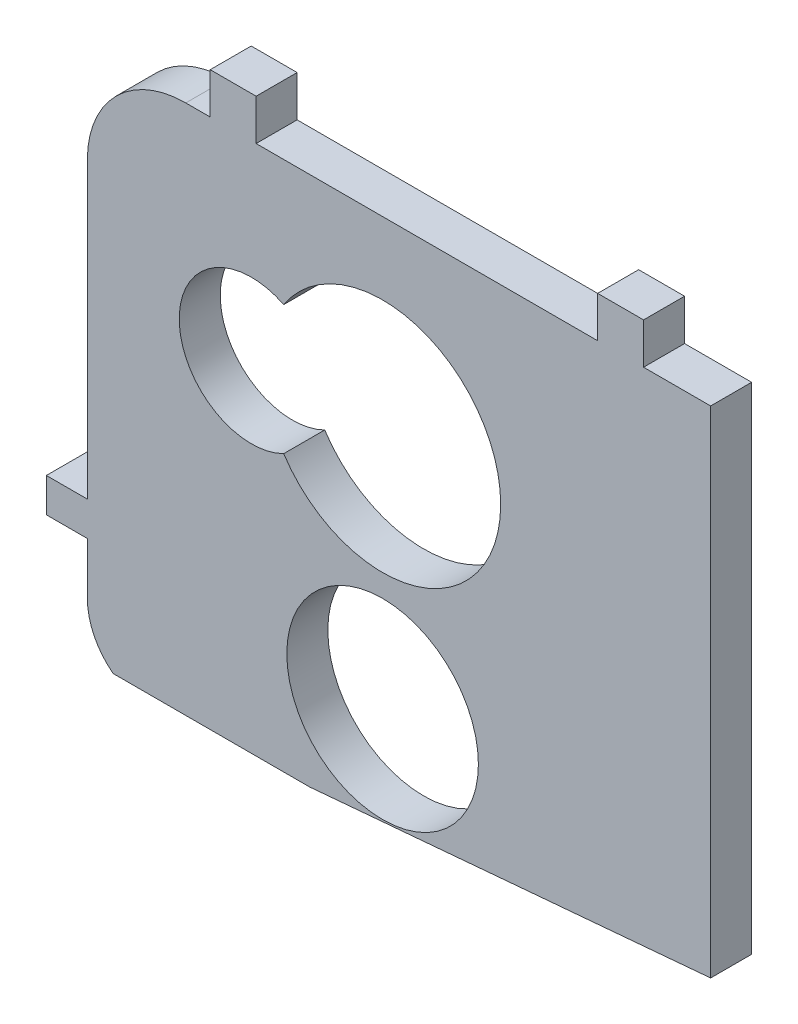
SolidWorks part; units mm, degrees
material "Balsa"
ref_plane "Front Plane" through (0, 0, 0) normal (0, 0, 1) x (1, 0, 0)
ref_plane "Top Plane" through (0, 0, 0) normal (0, 1, 0) x (1, 0, 0)
ref_plane "Right Plane" through (0, 0, 0) normal (1, 0, 0) x (0, 0, -1)
sketch "Sketch1" plane through (0, 0, 0) normal (0, 0, 1) x (1, 0, 0)
  line L0 (0, -1000.1535) -> (0, 48999.8465) construction
  line L1 (-2.8233, -4.0284) -> (-10.4313, -4.0284)
  line L2 (-1000, 0) -> (49000, 0) construction
  line L3 (12.7, 16.51) -> (-7.62, 16.51)
  line L4 (12.7, 16.51) -> (12.7, -2.6702)
  line L5 (8.3256, 18.0975) -> (10.1036, 18.0975)
  line L6 (12.7, -2.6702) -> (-8.6686, -4.5398)
  line L7 (-11.43, 12.7) -> (-11.43, -2.0094)
  line L8 (-6.6744, 16.51) -> (-4.8964, 16.51)
  line L9 (-6.6744, 16.51) -> (-6.6744, 18.0975)
  line L10 (-6.6744, 18.0975) -> (-4.8964, 18.0975)
  line L11 (-4.8964, 16.51) -> (-4.8964, 18.0975)
  line L12 (-11.43, 0) -> (-13.0175, 0)
  line L13 (-11.43, 0) -> (-11.43, 1.3208)
  line L14 (-11.43, 1.3208) -> (-13.0175, 1.3208)
  line L15 (-13.0175, 0) -> (-13.0175, 1.3208)
  line L16 (10.1036, 16.51) -> (10.1036, 18.0975)
  line L17 (8.3256, 16.51) -> (10.1036, 16.51)
  line L18 (8.3256, 16.51) -> (8.3256, 18.0975)
  circle A0 centre (0, 0) radius 3.7084
  arc A1 (-3.829, 6.6457) -> (-3.829, 11.6423) centre (0, 9.144) ccw
  arc A2 (-3.829, 11.6423) -> (-3.829, 6.6457) centre (-5.08, 9.144) ccw
  arc A3 (-7.62, 16.51) -> (-11.43, 12.7) centre (-7.62, 12.7) ccw
  arc A4 (-8.6686, -4.5398) -> (-11.43, -2.0094) centre (-8.89, -2.0094) cw
  dimension "D1" = 7.4168
  dimension "D4" = 7.366
  dimension "D3" = 9.144
  dimension "D5" = 5.588
  dimension "D9" = 3.81
  dimension "D10" = 11.43
  dimension "D14" = 1.5875
  dimension "D12" = 2.54
  dimension "D2" = 12.7
  dimension "D6" = 9.144
  dimension "D7" = 5.08
  dimension "D8" = 6.35
  dimension "D11" = 5
  dimension "D13" = 3.767
  dimension "D15" = 1.778
  dimension "D16" = 1.5875
  dimension "D17" = 1.3208
  dimension "D18" = 1.778
  dimension "D19" = 1.5875
extrude "Boss-Extrude1" add sketch "Sketch1" along normal blind 1.5875
